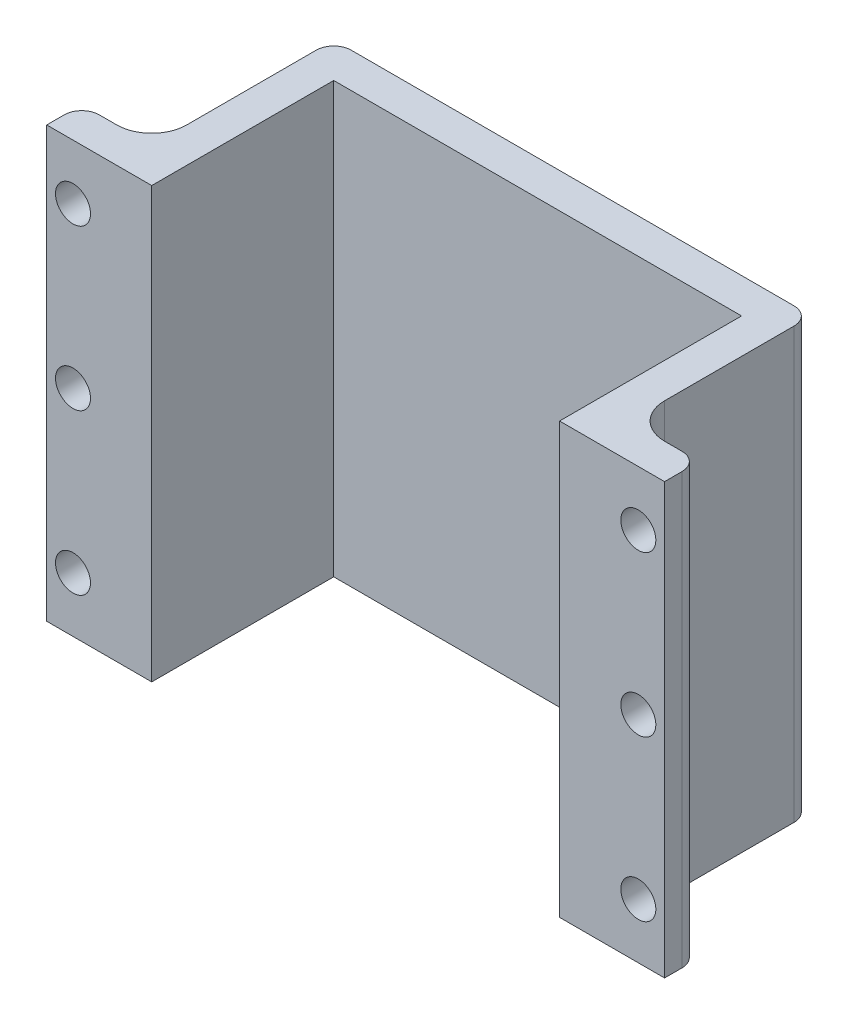
SolidWorks part; units mm, degrees
ref_plane "Front Plane" through (0, 0, 0) normal (0, 0, 1) x (1, 0, 0)
ref_plane "Top Plane" through (0, 0, 0) normal (0, 1, 0) x (1, 0, 0)
ref_plane "Right Plane" through (0, 0, 0) normal (1, 0, 0) x (0, 0, -1)
sketch "Sketch1" plane through (0, 0, 0) normal (0, 1, 0) x (1, 0, 0)
  line L0 (0, 0) -> (0, -85.5367) construction
  line L5 (-37, 0) -> (37, 0)
  line L7 (-40.175, 6.35) -> (40.175, 6.35)
  line L8 (43.35, 0) -> (43.35, 3.175)
  line L10 (43.35, 0) -> (43.35, -20.32)
  line L11 (30.65, -33.02) -> (37, -33.02)
  line L12 (37, 0) -> (37, -33.02)
  line L13 (30.65, -33.02) -> (56.05, -33.02)
  line L15 (49.7, -26.67) -> (52.875, -26.67)
  line L16 (56.05, -33.02) -> (56.05, -29.845)
  line L17 (-43.35, 0) -> (-43.35, -20.32)
  line L18 (-49.7, -26.67) -> (-52.875, -26.67)
  line L19 (-56.05, -33.02) -> (-56.05, -29.845)
  line L20 (-30.65, -33.02) -> (-56.05, -33.02)
  line L21 (-30.65, -33.02) -> (-37, -33.02)
  line L22 (-37, 0) -> (-37, -33.02)
  line L23 (-43.35, 0) -> (-43.35, 3.175)
  arc A0 (43.35, -20.32) -> (49.7, -26.67) centre (49.7, -20.32) ccw
  arc A1 (-43.35, -20.32) -> (-49.7, -26.67) centre (-49.7, -20.32) cw
  arc A2 (52.875, -26.67) -> (56.05, -29.845) centre (52.875, -29.845) cw
  arc A3 (-52.875, -26.67) -> (-56.05, -29.845) centre (-52.875, -29.845) ccw
  arc A4 (40.175, 6.35) -> (43.35, 3.175) centre (40.175, 3.175) cw
  arc A5 (-43.35, 3.175) -> (-40.175, 6.35) centre (-40.175, 3.175) cw
  point P20 (0, 0)
  point P21 (0, 0)
  point P24 (43.35, -26.67)
  point P27 (-43.35, -26.67)
  point P30 (56.05, -26.67)
  point P33 (-56.05, -26.67)
  point P36 (43.35, 6.35)
  point P39 (-43.35, 6.35)
  dimension "D7" = 6.35
  dimension "D8" = 3.175
  dimension "D9" = 3.175
  dimension "D1" = 33.02
  dimension "D2" = 6.35
  dimension "D4" = 6.35
  dimension "D5" = 12.7
  dimension "D6" = 37
extrude "Boss-Extrude1" add sketch "Sketch1" along normal blind 78
sketch "Sketch2" plane through (0, 0, 26.67) normal (0, 0, -1) x (-1, 0, 0)
  line L0 (-51.2875, 0) -> (-51.2875, 78) construction
  line L1 (-49.7, 0) -> (-52.875, 0) construction
  line L2 (-49.7, 78) -> (-52.875, 78) construction
  line L3 (51.2875, 0) -> (51.2875, 78) construction
  line L4 (49.7, 0) -> (52.875, 0) construction
  line L5 (49.7, 78) -> (52.875, 78) construction
  line L6 (0, 0) -> (0, 78) construction
  line L7 (40.175, 78) -> (-40.175, 78) construction
  line L8 (56.05, 39) -> (-56.05, 39) construction
  line L9 (56.05, 78) -> (56.05, 0) construction
  line L10 (-56.05, 78) -> (-56.05, 0) construction
  circle A0 centre (-51.2875, 10) radius 3.175
  circle A1 centre (-51.2875, 39) radius 3.175
  circle A2 centre (-51.2875, 68) radius 3.175
  circle A3 centre (51.2875, 68) radius 3.175
  circle A4 centre (51.2875, 39) radius 3.175
  circle A5 centre (51.2875, 10) radius 3.175
  point P25 (-57.1375, 10.5761)
  point P28 (-57.1375, 39)
  point P31 (-57.1375, 71.0231)
  dimension "D1" = 6.35
  dimension "D4" = 6.35
  dimension "D5" = 6.35
  dimension "D2" = 10
  dimension "D3" = 10
extrude "Cut-Extrude1" cut sketch "Sketch2" against normal up to next and the other way up to surface other way up to face at (0, 39, -6.35)
